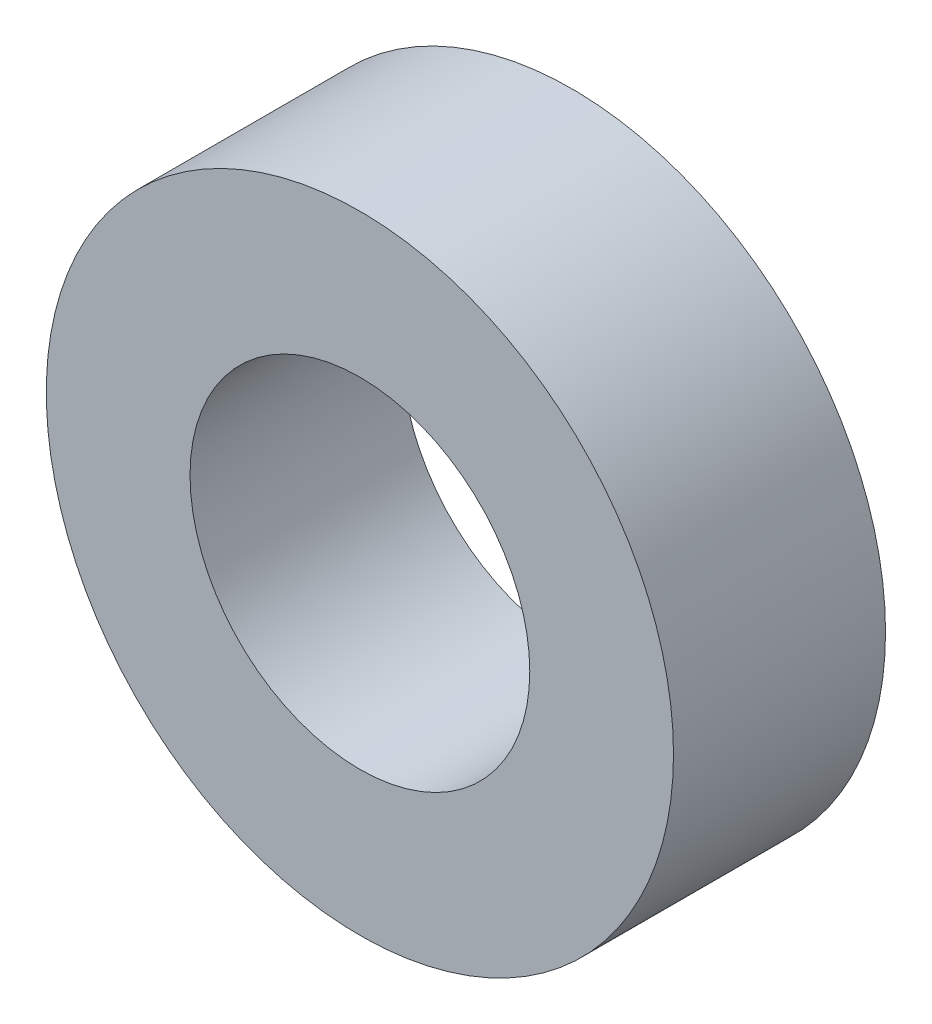
SolidWorks part; units mm, degrees
material "Brass"
ref_plane "Front Plane" through (0, 0, 0) normal (0, 0, 1) x (1, 0, 0)
ref_plane "Top Plane" through (0, 0, 0) normal (0, 1, 0) x (1, 0, 0)
ref_plane "Right Plane" through (0, 0, 0) normal (1, 0, 0) x (0, 0, -1)
sketch "Sketch1" plane through (0, 0, 0) normal (0, 0, 1) x (1, 0, 0)
  circle A0 centre (0, 0) radius 6
  circle A1 centre (0, 0) radius 3.25
  dimension "D1" = 12
  dimension "D2" = 6.5
extrude "Boss-Extrude1" add sketch "Sketch1" along normal mid plane 4.0565
